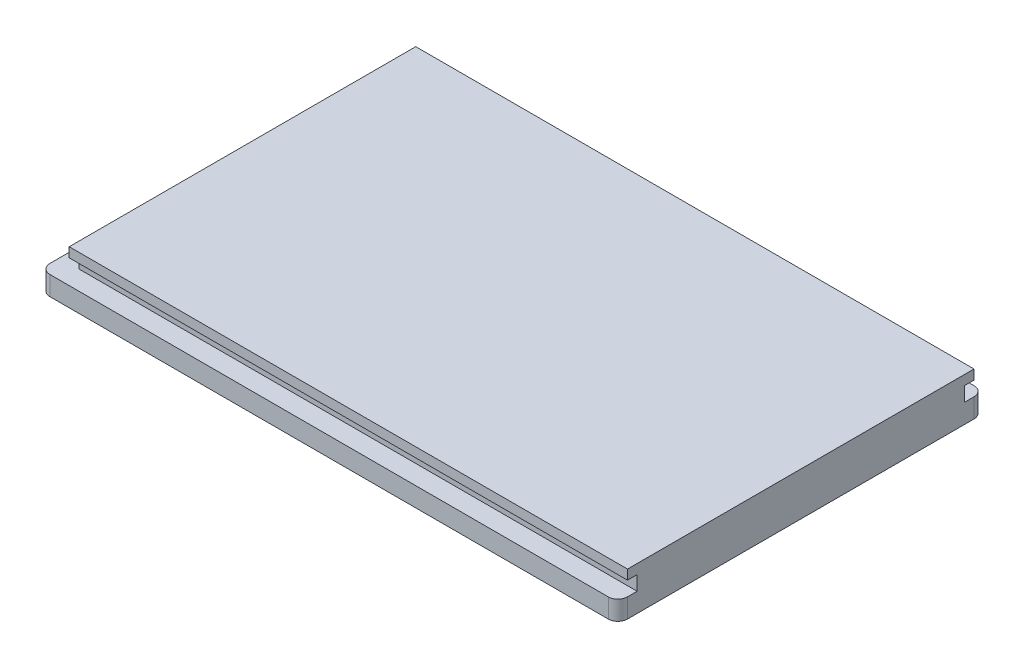
SolidWorks part; units mm, degrees
ref_plane "Front Plane" through (0, 0, 0) normal (0, 0, 1) x (1, 0, 0)
ref_plane "Top Plane" through (0, 0, 0) normal (0, 1, 0) x (1, 0, 0)
ref_plane "Right Plane" through (0, 0, 0) normal (1, 0, 0) x (0, 0, -1)
sketch "Sketch1" plane through (0, 0, 0) normal (0, 1, 0) x (1, 0, 0)
  line L1 (0, 0) -> (150, 0)
  line L2 (0, 0) -> (0, 95)
  line L3 (0, 95) -> (150, 95)
  line L4 (150, 0) -> (150, 95)
  dimension "D1" = 95
  dimension "D2" = 150
extrude "Boss-Extrude1" add sketch "Sketch1" along normal blind 5
sketch "Sketch2" plane through (0, 5, 0) normal (0, 1, 0) x (1, 0, 0)
  line L0 (0, 95) -> (0, 90) construction
  line L1 (0, 95) -> (0, 0) construction
  line L2 (0, 90) -> (5, 90) construction
  line L3 (5, 90) -> (150, 90)
  line L5 (150, 0) -> (150, 95) construction
  line L6 (150, 90) -> (150, 5)
  line L7 (150, 5) -> (5, 5)
  line L8 (5, 90) -> (5, 5)
  dimension "D1" = 5
extrude "Boss-Extrude2" add sketch "Sketch2" along normal blind 3.75
sketch "Sketch3" plane through (0, 8.75, 0) normal (0, 1, 0) x (1, 0, 0)
  line L0 (5, 90) -> (5, 92.5) construction
  line L1 (5, 5) -> (5, 2.5) construction
  line L2 (5, 2.5) -> (5, 92.5)
  line L4 (5, 2.5) -> (150, 2.5)
  line L6 (5, 92.5) -> (150, 92.5)
  line L7 (150, 2.5) -> (150, 92.5)
  line L8 (150, 5) -> (150, 90) construction
  dimension "D1" = 2.5
extrude "Boss-Extrude3" add sketch "Sketch3" along normal blind 2.5
fillet "Fillet2" radius 2.5 4 edges at (150, 2.5, 0) (150, 2.5, -95) (0, 2.5, 0) (0, 2.5, -95)
